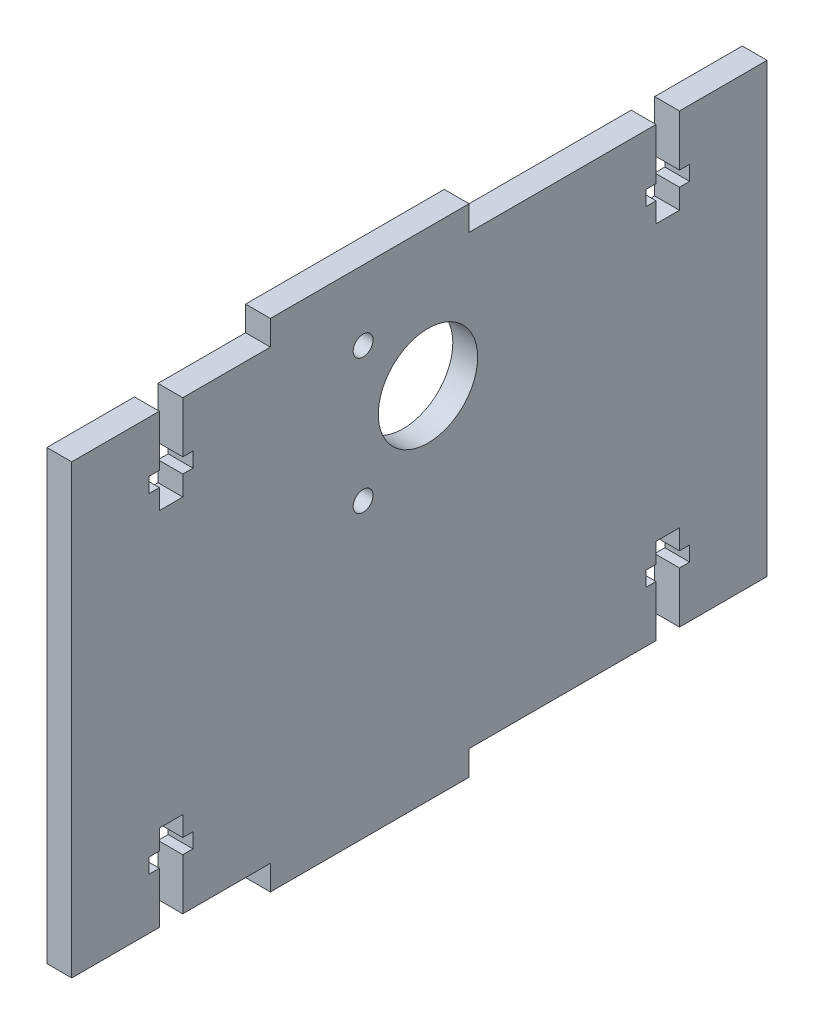
SolidWorks part; units mm, degrees
ref_plane "Front Plane" through (0, 0, 0) normal (0, 0, 1) x (1, 0, 0)
ref_plane "Top Plane" through (0, 0, 0) normal (0, 1, 0) x (1, 0, 0)
ref_plane "Right Plane" through (0, 0, 0) normal (1, 0, 0) x (0, 0, -1)
sketch "Sketch1" plane through (0, 0, 0) normal (1, 0, 0) x (0, 0, -1)
  line L1 (-44.45, -31.75) -> (44.45, -31.75)
  line L2 (-44.45, -31.75) -> (-44.45, 31.75)
  line L3 (-44.45, 31.75) -> (44.45, 31.75)
  line L4 (44.45, -31.75) -> (44.45, 31.75)
  line L5 (-44.45, -31.75) -> (44.45, 31.75) construction
  line L6 (-44.45, 31.75) -> (44.45, -31.75) construction
  point P0 (0, 0)
  dimension "D1" = 88.9
  dimension "D2" = 63.5
extrude "Boss-Extrude1" add sketch "Sketch1" along normal blind 3.175
sketch "Sketch2" plane through (3.175, 0, 0) normal (1, 0, 0) x (0, 0, -1)
  line L0 (-44.45, -31.75) -> (44.45, -31.75) construction
  line L1 (-44.45, -31.75) -> (44.45, -31.75) construction
  line L2 (-19.05, -31.75) -> (-19.05, -28.575) construction
  line L3 (-19.05, 31.75) -> (-19.05, 28.575) construction
  line L4 (44.45, -31.75) -> (6.35, -31.75)
  line L5 (-44.45, 0) -> (44.45, 0) construction
  line L6 (-44.45, 31.75) -> (-44.45, -31.75) construction
  line L7 (44.45, -31.75) -> (44.45, 31.75) construction
  line L8 (44.45, -31.75) -> (44.45, -28.575)
  line L9 (44.45, -28.575) -> (6.35, -28.575)
  line L10 (6.35, -31.75) -> (6.35, -28.575)
  line L11 (-19.05, 28.575) -> (-44.45, 28.575)
  line L12 (0, 31.75) -> (0, -31.75) construction
  line L13 (-19.05, 31.75) -> (-19.05, 28.575)
  line L14 (-19.05, 31.75) -> (-41.275, 31.75)
  line L15 (-44.45, 31.75) -> (-44.45, 28.575)
  line L16 (-44.45, 31.75) -> (-41.275, 31.75)
  line L17 (-44.45, -31.75) -> (-41.275, -31.75)
  line L18 (-44.45, -31.75) -> (-44.45, -28.575)
  line L19 (6.35, 31.75) -> (6.35, 28.575)
  line L20 (44.45, 28.575) -> (6.35, 28.575)
  line L21 (44.45, 31.75) -> (-44.45, 31.75) construction
  line L22 (44.45, 31.75) -> (44.45, 28.575)
  line L23 (44.45, 31.75) -> (6.35, 31.75)
  line L31 (-19.05, -31.75) -> (-41.275, -31.75)
  line L32 (-19.05, -31.75) -> (-19.05, -28.575)
  line L33 (-19.05, -28.575) -> (-44.45, -28.575)
  point P6 (0, -31.75)
  dimension "D1" = 3.175
  dimension "D2" = 19.05
  dimension "D3" = 25.4
extrude "Cut-Extrude1" cut sketch "Sketch2" against normal through all
sketch "Sketch3" plane through (3.175, 0, 0) normal (1, 0, 0) x (0, 0, -1)
  line L0 (-30.25, -17.575) -> (-30.25, -20.125)
  line L1 (-30.25, -17.575) -> (-33.25, -17.575)
  line L2 (-30.25, -28.575) -> (-33.25, -28.575)
  line L3 (-33.25, -17.575) -> (-33.25, -20.125)
  line L4 (-30.25, -17.575) -> (-33.25, -28.575) construction
  line L5 (-30.25, -28.575) -> (-33.25, -17.575) construction
  line L6 (-33.25, -22.025) -> (-33.25, -28.575)
  line L7 (-34.55, -22.025) -> (-34.55, -20.125)
  line L8 (-34.55, -22.025) -> (-33.25, -22.025)
  line L9 (-28.95, -22.025) -> (-28.95, -20.125)
  line L10 (-34.55, -20.125) -> (-33.25, -20.125)
  line L11 (-34.55, -22.025) -> (-28.95, -20.125) construction
  line L12 (-28.95, -22.025) -> (-34.55, -20.125) construction
  line L13 (-30.25, -22.025) -> (-30.25, -28.575)
  line L14 (-33.25, -20.125) -> (-33.25, -22.025) construction
  line L15 (-30.25, -17.575) -> (-30.25, -22.025) construction
  line L16 (-30.25, -22.025) -> (-28.95, -22.025)
  line L17 (-30.25, -20.125) -> (-28.95, -20.125)
  line L18 (-33.25, -20.125) -> (-30.25, -20.125) construction
  line L19 (-30.25, -22.025) -> (-33.25, -22.025) construction
  line L20 (-19.05, -28.575) -> (-44.45, -28.575) construction
  line L21 (33.25, -17.575) -> (33.25, -20.125)
  line L22 (33.25, -17.575) -> (30.25, -17.575)
  line L23 (33.25, -28.575) -> (30.25, -28.575)
  line L24 (30.25, -17.575) -> (30.25, -20.125)
  line L25 (33.25, -17.575) -> (30.25, -28.575) construction
  line L26 (33.25, -28.575) -> (30.25, -17.575) construction
  line L27 (30.25, -22.025) -> (30.25, -28.575)
  line L28 (28.95, -22.025) -> (28.95, -20.125)
  line L29 (28.95, -22.025) -> (30.25, -22.025)
  line L30 (34.55, -22.025) -> (34.55, -20.125)
  line L31 (28.95, -20.125) -> (30.25, -20.125)
  line L32 (28.95, -22.025) -> (34.55, -20.125) construction
  line L33 (34.55, -22.025) -> (28.95, -20.125) construction
  line L34 (33.25, -22.025) -> (33.25, -28.575)
  line L35 (30.25, -20.125) -> (30.25, -22.025) construction
  line L36 (33.25, -17.575) -> (33.25, -22.025) construction
  line L37 (33.25, -22.025) -> (34.55, -22.025)
  line L38 (33.25, -20.125) -> (34.55, -20.125)
  line L39 (30.25, -20.125) -> (33.25, -20.125) construction
  line L40 (33.25, -22.025) -> (30.25, -22.025) construction
  line L41 (44.45, -28.575) -> (6.35, -28.575) construction
  line L42 (44.45, -28.575) -> (44.45, 28.575) construction
  line L43 (-44.45, 0) -> (44.45, 0) construction
  line L44 (-44.45, 28.575) -> (-44.45, -28.575) construction
  line L45 (33.25, 22.025) -> (30.25, 22.025) construction
  line L46 (30.25, 20.125) -> (33.25, 20.125) construction
  line L47 (33.25, 17.575) -> (33.25, 22.025) construction
  line L48 (30.25, 20.125) -> (30.25, 22.025) construction
  line L49 (34.55, 22.025) -> (28.95, 20.125) construction
  line L50 (28.95, 22.025) -> (34.55, 20.125) construction
  line L51 (33.25, 28.575) -> (30.25, 17.575) construction
  line L52 (33.25, 17.575) -> (30.25, 28.575) construction
  line L53 (33.25, 20.125) -> (34.55, 20.125)
  line L54 (33.25, 22.025) -> (34.55, 22.025)
  line L55 (33.25, 22.025) -> (33.25, 28.575)
  line L56 (28.95, 20.125) -> (30.25, 20.125)
  line L57 (34.55, 22.025) -> (34.55, 20.125)
  line L58 (28.95, 22.025) -> (30.25, 22.025)
  line L59 (28.95, 22.025) -> (28.95, 20.125)
  line L60 (30.25, 22.025) -> (30.25, 28.575)
  line L61 (30.25, 17.575) -> (30.25, 20.125)
  line L62 (33.25, 28.575) -> (30.25, 28.575)
  line L63 (33.25, 17.575) -> (30.25, 17.575)
  line L64 (33.25, 17.575) -> (33.25, 20.125)
  line L65 (-30.25, 22.025) -> (-33.25, 22.025) construction
  line L66 (-33.25, 20.125) -> (-30.25, 20.125) construction
  line L67 (-30.25, 17.575) -> (-30.25, 22.025) construction
  line L68 (-33.25, 20.125) -> (-33.25, 22.025) construction
  line L69 (-28.95, 22.025) -> (-34.55, 20.125) construction
  line L70 (-34.55, 22.025) -> (-28.95, 20.125) construction
  line L71 (-30.25, 28.575) -> (-33.25, 17.575) construction
  line L72 (-30.25, 17.575) -> (-33.25, 28.575) construction
  line L73 (-30.25, 20.125) -> (-28.95, 20.125)
  line L74 (-30.25, 22.025) -> (-28.95, 22.025)
  line L75 (-30.25, 22.025) -> (-30.25, 28.575)
  line L76 (-34.55, 20.125) -> (-33.25, 20.125)
  line L77 (-28.95, 22.025) -> (-28.95, 20.125)
  line L78 (-34.55, 22.025) -> (-33.25, 22.025)
  line L79 (-34.55, 22.025) -> (-34.55, 20.125)
  line L80 (-33.25, 22.025) -> (-33.25, 28.575)
  line L81 (-33.25, 17.575) -> (-33.25, 20.125)
  line L82 (-30.25, 28.575) -> (-33.25, 28.575)
  line L83 (-30.25, 17.575) -> (-33.25, 17.575)
  line L84 (-30.25, 17.575) -> (-30.25, 20.125)
  point P0 (-31.75, -28.575)
  point P5 (-31.75, -21.075)
  point P17 (31.75, -28.575)
  point P22 (31.75, -21.075)
  point P52 (31.75, 21.075)
  point P53 (31.75, 28.575)
  point P66 (-31.75, 21.075)
  point P67 (-31.75, 28.575)
  dimension "D1" = 3
  dimension "D2" = 11
  dimension "D3" = 5.6
  dimension "D4" = 1.9
  dimension "D5" = 3.5
  dimension "D6" = 3
  dimension "D7" = 11
  dimension "D8" = 5.6
  dimension "D9" = 1.9
  dimension "D10" = 3.5
  dimension "D11" = 12.7
extrude "Cut-Extrude2" cut sketch "Sketch3" against normal through all
sketch "Sketch4" plane through (3.175, 0, 0) normal (1, 0, 0) x (0, 0, -1)
  circle A0 centre (1.0937, 14.225) radius 6.35
  circle A1 centre (-7.1984, 5.625) radius 1.27
  circle A3 centre (-7.1984, 22.825) radius 1.27
  dimension "D1" = 12.7
  dimension "D2" = 2.54
extrude "Cut-Extrude3" cut sketch "Sketch4" against normal through all
